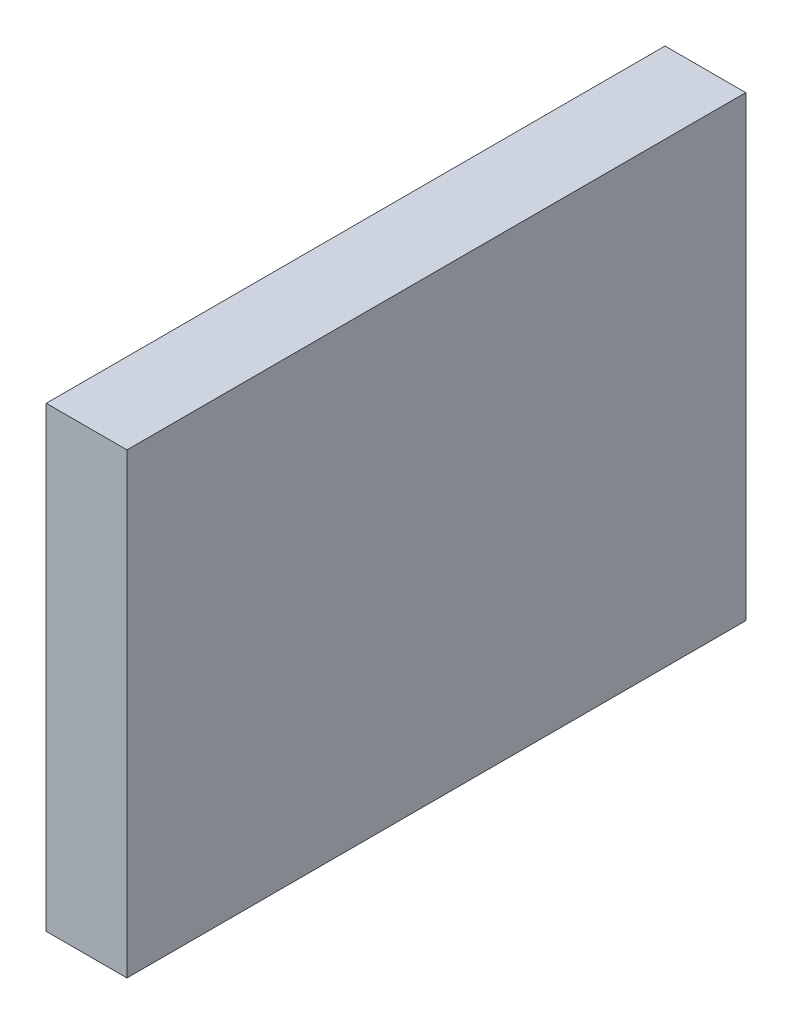
SolidWorks part; units mm, degrees
ref_plane "Front Plane" through (0, 0, 0) normal (0, 0, 1) x (1, 0, 0)
ref_plane "Top Plane" through (0, 0, 0) normal (0, 1, 0) x (1, 0, 0)
ref_plane "Right Plane" through (0, 0, 0) normal (1, 0, 0) x (0, 0, -1)
sketch "Sketch1" plane through (0, 0, 0) normal (0, 0, 1) x (1, 0, 0)
  line L1 (38.1, -215.9) -> (-38.1, -215.9)
  line L2 (38.1, -215.9) -> (38.1, 215.9)
  line L3 (38.1, 215.9) -> (-38.1, 215.9)
  line L4 (-38.1, -215.9) -> (-38.1, 215.9)
  line L5 (38.1, -215.9) -> (-38.1, 215.9) construction
  line L6 (38.1, 215.9) -> (-38.1, -215.9) construction
  point P0 (0, 0)
  dimension "D1" = 76.2
  dimension "D2" = 431.8
extrude "Boss-Extrude1" add sketch "Sketch1" along normal blind 584.2
